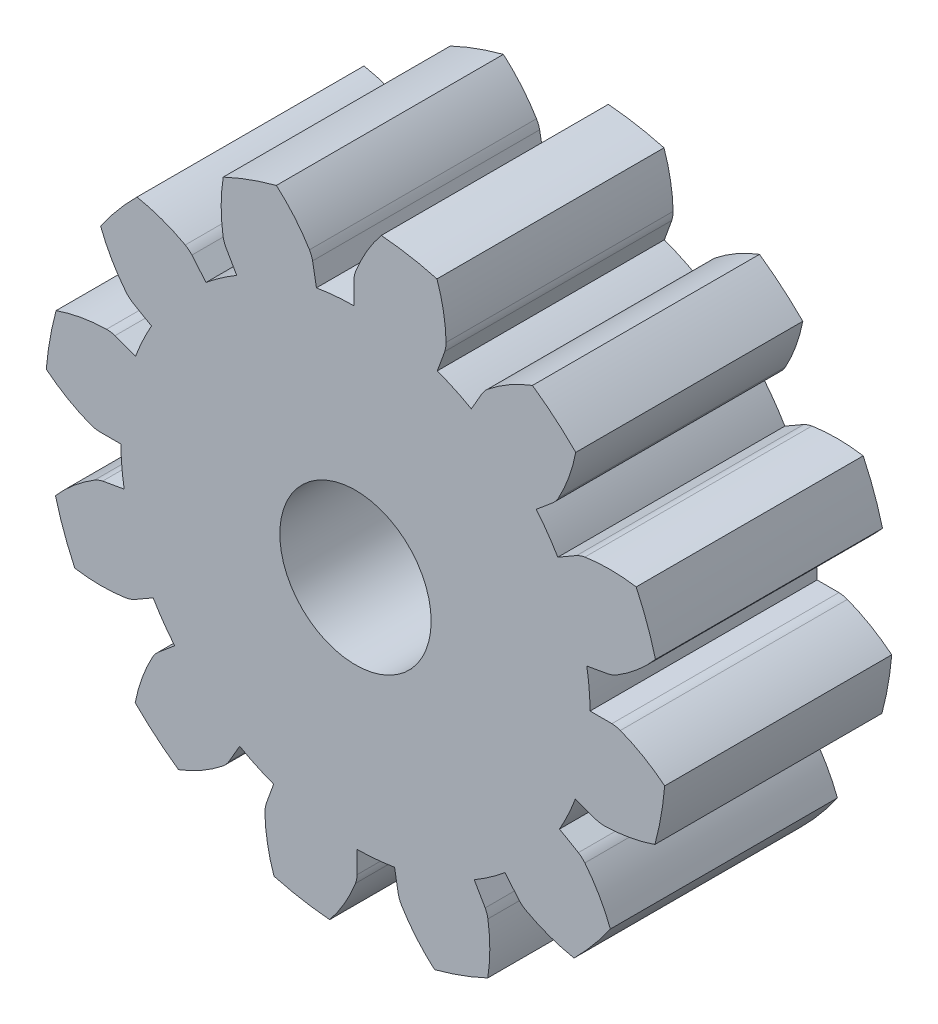
SolidWorks part; units mm, degrees
ref_plane "Front Plane" through (0, 0, 0) normal (0, 0, 1) x (1, 0, 0)
ref_plane "Top Plane" through (0, 0, 0) normal (0, 1, 0) x (1, 0, 0)
ref_plane "Right Plane" through (0, 0, 0) normal (1, 0, 0) x (0, 0, -1)
sketch "Sketch1" plane through (0, 0, 0) normal (0, 0, 1) x (1, 0, 0)
  line L0 (0, 5.8931) -> (0, -6.7835) construction
  line L1 (-10.3696, 0) -> (9.5981, 0) construction
  line L2 (-1.6968, 6.5612) -> (0, 0) construction
  line L3 (0, 0) -> (1.707, -6.6006) construction
  line L4 (-0.8484, 3.2806) -> (0, 3.5) construction
  line L5 (0, 3.5) -> (1.1971, 3.2889) construction
  line L6 (0, 0) -> (0.5985, 3.3945) construction
  line L7 (-0.0223, 3.3884) -> (-0.0223, 3.0999)
  line L8 (1.1799, 3.1765) -> (1.0812, 2.9053)
  line L9 (1.6749, 2.9456) -> (1.5306, 2.6958)
  line L10 (2.61, 2.161) -> (2.389, 1.9755)
  line L11 (2.9233, 1.7135) -> (2.6735, 1.5693)
  line L12 (3.3408, 0.5664) -> (3.0567, 0.5163)
  line L13 (3.3884, 0.0223) -> (3.0999, 0.0223)
  line L14 (3.1765, -1.1799) -> (2.9053, -1.0812)
  line L15 (2.9456, -1.6749) -> (2.6958, -1.5306)
  line L16 (2.161, -2.61) -> (1.9755, -2.389)
  line L17 (1.7135, -2.9233) -> (1.5693, -2.6735)
  line L18 (0.5664, -3.3408) -> (0.5163, -3.0567)
  line L19 (0.0223, -3.3884) -> (0.0223, -3.0999)
  line L20 (-1.1799, -3.1765) -> (-1.0812, -2.9053)
  line L21 (-1.6749, -2.9456) -> (-1.5306, -2.6958)
  line L22 (-2.61, -2.161) -> (-2.389, -1.9755)
  line L23 (-2.9233, -1.7135) -> (-2.6735, -1.5693)
  line L24 (-3.3408, -0.5664) -> (-3.0567, -0.5163)
  line L25 (-3.3884, -0.0223) -> (-3.0999, -0.0223)
  line L26 (-3.1765, 1.1799) -> (-2.9053, 1.0812)
  line L27 (-2.9456, 1.6749) -> (-2.6958, 1.5306)
  line L28 (-2.161, 2.61) -> (-1.9755, 2.389)
  line L29 (-1.7135, 2.9233) -> (-1.5693, 2.6735)
  line L30 (-0.5664, 3.3408) -> (-0.5163, 3.0567)
  circle A0 centre (0, 0) radius 3.5 construction
  arc A1 (-0.0223, 3.0999) -> (-0.5163, 3.0567) centre (0, 0) ccw
  arc A2 (1.0768, 3.9561) -> (0.3412, 4.0858) centre (0, 0) ccw
  circle A3 centre (0, 0) radius 3.3885 construction
  arc A4 (0, 3.5) -> (0.3412, 4.0858) centre (2.0489, 2.6989) cw
  arc A5 (0, 3.5) -> (-0.0223, 3.3884) centre (0.3672, 3.3686) ccw
  arc A6 (1.1971, 3.2889) -> (1.0768, 3.9561) centre (-1.0023, 3.2369) ccw
  arc A7 (1.1971, 3.2889) -> (1.1799, 3.1765) centre (0.8071, 3.291) cw
  arc A8 (0, 4.1) -> (4.1, 0) centre (0, 0) ccw construction
  arc A9 (1.75, 3.0311) -> (1.6749, 2.9456) centre (2.0023, 2.7337) ccw
  arc A10 (1.75, 3.0311) -> (2.3384, 3.3678) centre (3.1239, 1.3128) cw
  arc A11 (2.9106, 2.8876) -> (2.3384, 3.3678) centre (0, 0) ccw
  arc A12 (2.6812, 2.2498) -> (2.9106, 2.8876) centre (0.7504, 3.3044) ccw
  arc A13 (2.6812, 2.2498) -> (2.61, 2.161) centre (2.3444, 2.4466) cw
  arc A14 (3.0311, 1.75) -> (2.9233, 1.7135) centre (3.1009, 1.3663) ccw
  arc A15 (3.0311, 1.75) -> (3.709, 1.7474) centre (3.3618, -0.425) cw
  arc A16 (3.9645, 1.0455) -> (3.709, 1.7474) centre (0, 0) ccw
  arc A17 (3.4468, 0.6078) -> (3.9645, 1.0455) centre (2.3021, 2.4865) ccw
  arc A18 (3.4468, 0.6078) -> (3.3408, 0.5664) centre (3.2536, 0.9466) cw
  arc A19 (3.5, 0) -> (3.3884, 0.0223) centre (3.3686, -0.3672) ccw
  arc A20 (3.5, 0) -> (4.0858, -0.3412) centre (2.6989, -2.0489) cw
  arc A21 (3.9561, -1.0768) -> (4.0858, -0.3412) centre (0, 0) ccw
  arc A22 (3.2889, -1.1971) -> (3.9561, -1.0768) centre (3.2369, 1.0023) ccw
  arc A23 (3.2889, -1.1971) -> (3.1765, -1.1799) centre (3.291, -0.8071) cw
  arc A24 (3.0311, -1.75) -> (2.9456, -1.6749) centre (2.7337, -2.0023) ccw
  arc A25 (3.0311, -1.75) -> (3.3678, -2.3384) centre (1.3128, -3.1239) cw
  arc A26 (2.8876, -2.9106) -> (3.3678, -2.3384) centre (0, 0) ccw
  arc A27 (2.2498, -2.6812) -> (2.8876, -2.9106) centre (3.3044, -0.7504) ccw
  arc A28 (2.2498, -2.6812) -> (2.161, -2.61) centre (2.4466, -2.3444) cw
  arc A29 (1.75, -3.0311) -> (1.7135, -2.9233) centre (1.3663, -3.1009) ccw
  arc A30 (1.75, -3.0311) -> (1.7474, -3.709) centre (-0.425, -3.3618) cw
  arc A31 (1.0455, -3.9645) -> (1.7474, -3.709) centre (0, 0) ccw
  arc A32 (0.6078, -3.4468) -> (1.0455, -3.9645) centre (2.4865, -2.3021) ccw
  arc A33 (0.6078, -3.4468) -> (0.5664, -3.3408) centre (0.9466, -3.2536) cw
  arc A34 (0, -3.5) -> (0.0223, -3.3884) centre (-0.3672, -3.3686) ccw
  arc A35 (0, -3.5) -> (-0.3412, -4.0858) centre (-2.0489, -2.6989) cw
  arc A36 (-1.0768, -3.9561) -> (-0.3412, -4.0858) centre (0, 0) ccw
  arc A37 (-1.1971, -3.2889) -> (-1.0768, -3.9561) centre (1.0023, -3.2369) ccw
  arc A38 (-1.1971, -3.2889) -> (-1.1799, -3.1765) centre (-0.8071, -3.291) cw
  arc A39 (-1.75, -3.0311) -> (-1.6749, -2.9456) centre (-2.0023, -2.7337) ccw
  arc A40 (-1.75, -3.0311) -> (-2.3384, -3.3678) centre (-3.1239, -1.3128) cw
  arc A41 (-2.9106, -2.8876) -> (-2.3384, -3.3678) centre (0, 0) ccw
  arc A42 (-2.6812, -2.2498) -> (-2.9106, -2.8876) centre (-0.7504, -3.3044) ccw
  arc A43 (-2.6812, -2.2498) -> (-2.61, -2.161) centre (-2.3444, -2.4466) cw
  arc A44 (-3.0311, -1.75) -> (-2.9233, -1.7135) centre (-3.1009, -1.3663) ccw
  arc A45 (-3.0311, -1.75) -> (-3.709, -1.7474) centre (-3.3618, 0.425) cw
  arc A46 (-3.9645, -1.0455) -> (-3.709, -1.7474) centre (0, 0) ccw
  arc A47 (-3.4468, -0.6078) -> (-3.9645, -1.0455) centre (-2.3021, -2.4865) ccw
  arc A48 (-3.4468, -0.6078) -> (-3.3408, -0.5664) centre (-3.2536, -0.9466) cw
  arc A49 (-3.5, 0) -> (-3.3884, -0.0223) centre (-3.3686, 0.3672) ccw
  arc A50 (-3.5, 0) -> (-4.0858, 0.3412) centre (-2.6989, 2.0489) cw
  arc A51 (-3.9561, 1.0768) -> (-4.0858, 0.3412) centre (0, 0) ccw
  arc A52 (-3.2889, 1.1971) -> (-3.9561, 1.0768) centre (-3.2369, -1.0023) ccw
  arc A53 (-3.2889, 1.1971) -> (-3.1765, 1.1799) centre (-3.291, 0.8071) cw
  arc A54 (-3.0311, 1.75) -> (-2.9456, 1.6749) centre (-2.7337, 2.0023) ccw
  arc A55 (-3.0311, 1.75) -> (-3.3678, 2.3384) centre (-1.3128, 3.1239) cw
  arc A56 (-2.8876, 2.9106) -> (-3.3678, 2.3384) centre (0, 0) ccw
  arc A57 (-2.2498, 2.6812) -> (-2.8876, 2.9106) centre (-3.3044, 0.7504) ccw
  arc A58 (-2.2498, 2.6812) -> (-2.161, 2.61) centre (-2.4466, 2.3444) cw
  arc A59 (-1.75, 3.0311) -> (-1.7135, 2.9233) centre (-1.3663, 3.1009) ccw
  arc A60 (-1.75, 3.0311) -> (-1.7474, 3.709) centre (0.425, 3.3618) cw
  arc A61 (-1.0455, 3.9645) -> (-1.7474, 3.709) centre (0, 0) ccw
  arc A62 (-0.6078, 3.4468) -> (-1.0455, 3.9645) centre (-2.4865, 2.3021) ccw
  arc A63 (-0.6078, 3.4468) -> (-0.5664, 3.3408) centre (-0.9466, 3.2536) cw
  arc A64 (-1.5693, 2.6735) -> (-1.9755, 2.389) centre (0, 0) ccw
  arc A65 (-2.6958, 1.5306) -> (-2.9053, 1.0812) centre (0, 0) ccw
  arc A66 (-3.0999, -0.0223) -> (-3.0567, -0.5163) centre (0, 0) ccw
  arc A67 (-2.6735, -1.5693) -> (-2.389, -1.9755) centre (0, 0) ccw
  arc A68 (-1.5306, -2.6958) -> (-1.0812, -2.9053) centre (0, 0) ccw
  arc A69 (0.0223, -3.0999) -> (0.5163, -3.0567) centre (0, 0) ccw
  arc A70 (1.5693, -2.6735) -> (1.9755, -2.389) centre (0, 0) ccw
  arc A71 (2.6958, -1.5306) -> (2.9053, -1.0812) centre (0, 0) ccw
  arc A72 (3.0999, 0.0223) -> (3.0567, 0.5163) centre (0, 0) ccw
  arc A73 (2.6735, 1.5693) -> (2.389, 1.9755) centre (0, 0) ccw
  arc A74 (1.5306, 2.6958) -> (1.0812, 2.9053) centre (0, 0) ccw
  circle A75 centre (0, 0) radius 1
  point P10 (0, 3.5)
  point P15 (1.1971, 3.2889)
  point P16 (2.2498, 2.6812)
  point P17 (3.0311, 1.75)
  point P18 (3.4468, 0.6078)
  point P19 (3.4468, -0.6078)
  point P20 (3.0311, -1.75)
  point P21 (2.2498, -2.6812)
  point P22 (1.1971, -3.2889)
  point P23 (0, -3.5)
  point P24 (-1.1971, -3.2889)
  point P25 (-2.2498, -2.6812)
  point P26 (-3.0311, -1.75)
  point P27 (-3.4468, -0.6078)
  point P28 (-3.4468, 0.6078)
  point P29 (-3.0311, 1.75)
  point P30 (-2.2498, 2.6812)
  point P31 (-1.1971, 3.2889)
  point P32 (0, 0)
  point P180 (0, 0)
  dimension "D1" = 7
  dimension "D2" = 0.6
  dimension "D3" = 0.4
  dimension "D6" = 2.2
  dimension "D7" = 0.39
  dimension "D9" = 2
  dimension "D4" = 14.5
  dimension "D5" = 18
  dimension "D8" = 12
extrude "Boss-Extrude1" add sketch "Sketch1" along normal mid plane 3
